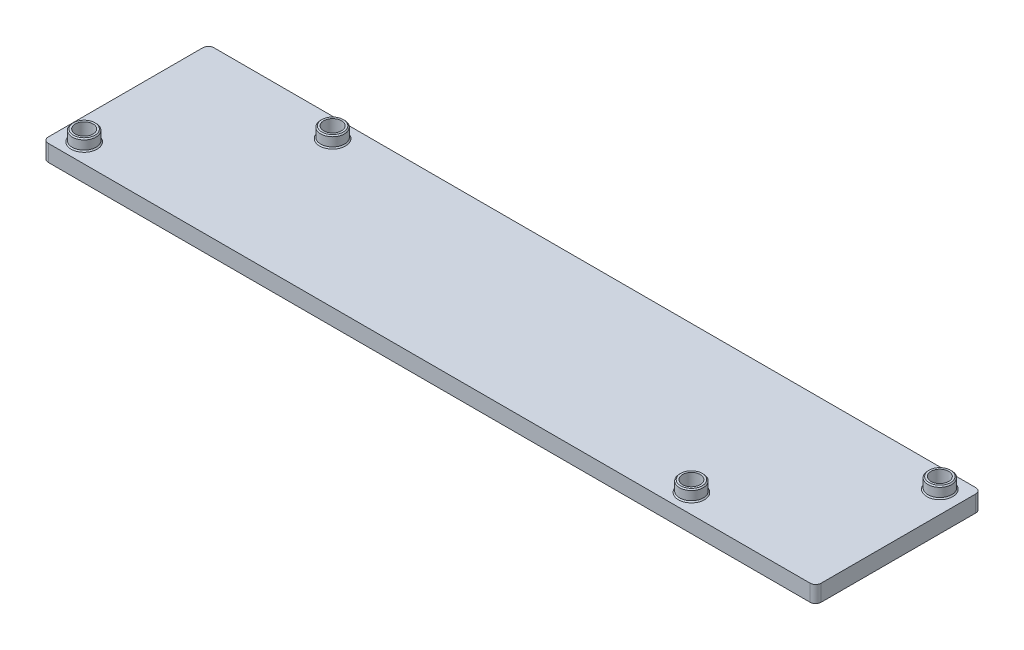
SolidWorks part; units mm, degrees
material "ABS"
ref_plane "Plan de face" through (0, 0, 0) normal (0, 0, 1) x (1, 0, 0)
ref_plane "Plan de dessus" through (0, 0, 0) normal (0, 1, 0) x (1, 0, 0)
ref_plane "Plan de droite" through (0, 0, 0) normal (1, 0, 0) x (0, 0, -1)
sketch "Esquisse1" plane through (0, 0, 0) normal (0, 1, 0) x (1, 0, 0)
  line L0 (4, 3.5) -> (114, 3.5) construction
  line L1 (0, 30) -> (140, 30)
  line L2 (0, 30) -> (0, 0)
  line L3 (0, 0) -> (140, 0)
  line L4 (140, 30) -> (140, 0)
  line L5 (4, 3.5) -> (26, 26.5) construction
  line L6 (114, 3.5) -> (136, 26.5) construction
  line L7 (26, 26.5) -> (136, 26.5) construction
  circle A0 centre (4, 3.5) radius 1.6
  circle A1 centre (26, 26.5) radius 1.6
  circle A2 centre (114, 3.5) radius 1.6
  circle A3 centre (136, 26.5) radius 1.6
  dimension "D1" = 23
  dimension "D4" = 3.5
  dimension "D5" = 3.5
  dimension "D7" = 4
  dimension "D8" = 3.2
  dimension "D2" = 22
  dimension "D3" = 110
  dimension "D6" = 4
  dimension "D9" = 30
  dimension "D10" = 140
extrude "Boss.-Extru.1" add sketch "Esquisse1" along normal blind 3
sketch "Esquisse2" plane through (0, 3, 0) normal (0, 1, 0) x (1, 0, 0)
  circle A0 centre (4, 3.5) radius 2.15
  circle A1 centre (26, 26.5) radius 2.15
  circle A2 centre (114, 3.5) radius 2.15
  circle A3 centre (136, 26.5) radius 2.15
  circle A4 centre (4, 3.5) radius 1.6 construction
  circle A5 centre (26, 26.5) radius 1.6 construction
  circle A6 centre (114, 3.5) radius 1.6 construction
  circle A7 centre (136, 26.5) radius 1.6 construction
  circle A8 centre (4, 3.5) radius 1.6
  circle A9 centre (26, 26.5) radius 1.6
  circle A10 centre (114, 3.5) radius 1.6
  circle A11 centre (136, 26.5) radius 1.6
  dimension "D1" = 4.3
extrude "Boss.-Extru.2" add sketch "Esquisse2" along normal blind 2
chamfer "Chanfrein1" distance 0.2 angle 45 8 edges at (26, 3, -24.35) (26, 5, -24.35) (4, 3, -1.35) (4, 5, -1.35) (136, 3, -24.35) (136, 5, -24.35) (114, 3, -1.35) (114, 5, -1.35)
chamfer "Chanfrein2" distance 1.5 angle 45 4 edges at (136, 0, -24.9) (114, 0, -1.9) (26, 0, -24.9) (4, 0, -1.9)
fillet "Congé1" radius 1 4 edges at (0, 1.5, 0) (0, 1.5, -30) (140, 1.5, -30) (140, 1.5, 0)
